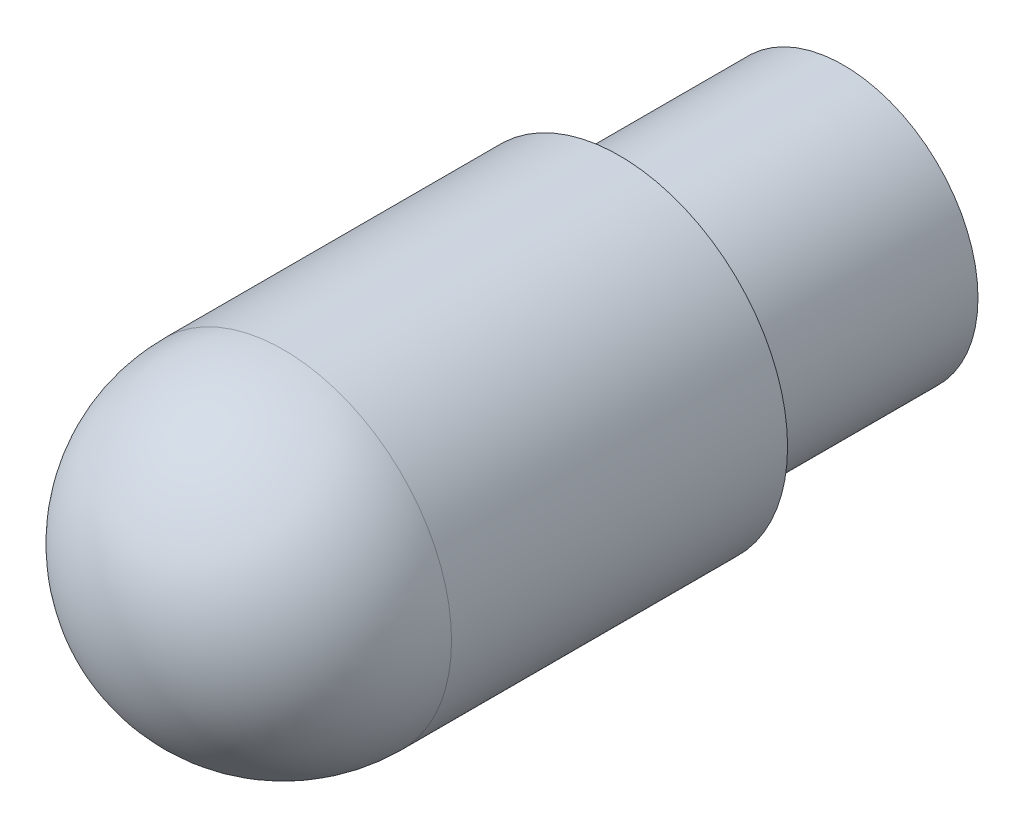
SolidWorks part; units mm, degrees
ref_plane "Front Plane" through (0, 0, 0) normal (0, 0, 1) x (1, 0, 0)
ref_plane "Top Plane" through (0, 0, 0) normal (0, 1, 0) x (1, 0, 0)
ref_plane "Right Plane" through (0, 0, 0) normal (1, 0, 0) x (0, 0, -1)
sketch "Sketch1" plane through (0, 0, 0) normal (0, 1, 0) x (1, 0, 0)
  line L12 (-7.5, 0) -> (-7.5, 15)
  line L13 (-7.5, 15) -> (-6, 15)
  line L15 (0, 15) -> (0, 25)
  line L16 (0, 25) -> (-6, 25)
  line L17 (-6, 25) -> (-6, 15)
  line L18 (0, 15) -> (0, -7.5)
  arc A2 (-7.5, 0) -> (0, -7.5) centre (0, 0) ccw
revolve "Revolve3" add sketch "Sketch1" angle 360 about L18
